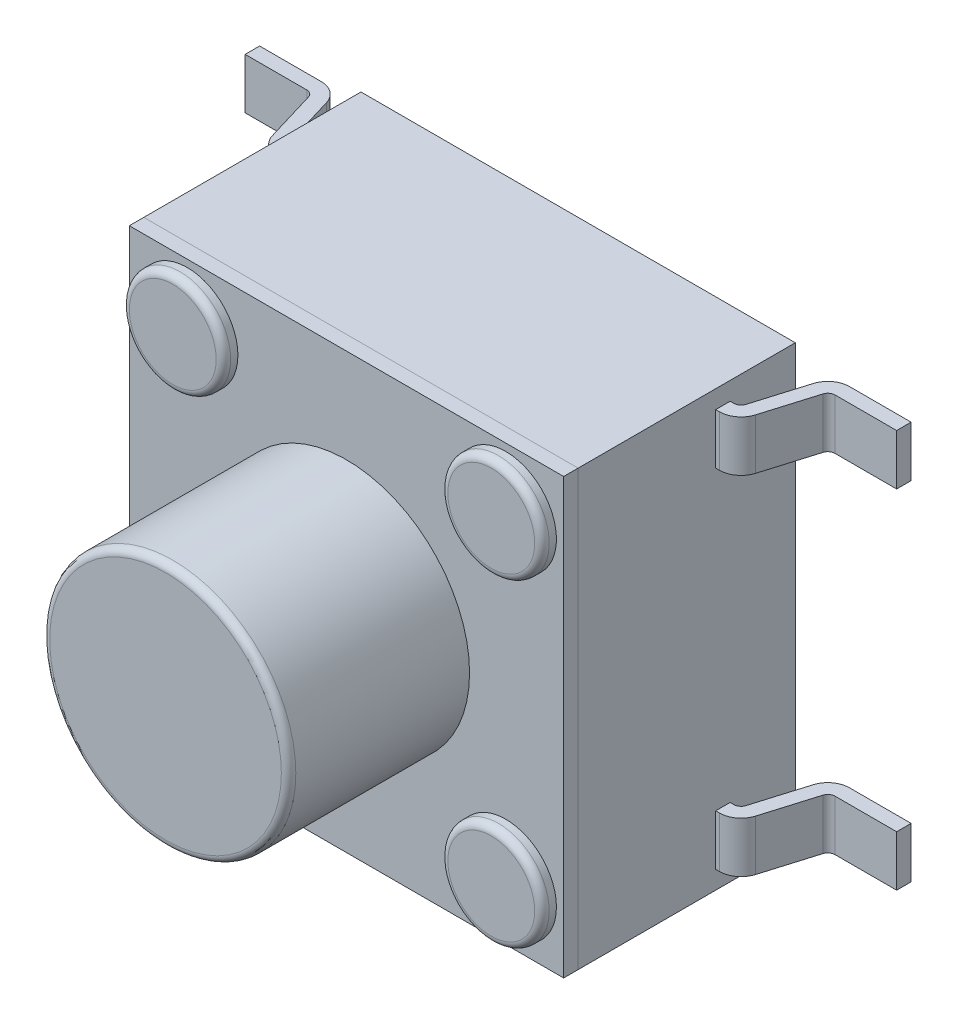
SolidWorks part; units mm, degrees
ref_plane "前视基准面" through (0, 0, 0) normal (0, 0, 1) x (1, 0, 0)
ref_plane "上视基准面" through (0, 0, 0) normal (0, 1, 0) x (1, 0, 0)
ref_plane "右视基准面" through (0, 0, 0) normal (1, 0, 0) x (0, 0, -1)
ref_plane "基准面1" through (0, 0, 0.1) normal (0, 0, 1) x (1, 0, 0)
sketch "草图2" plane through (0, 0, 0.1) normal (0, 0, 1) x (1, 0, 0)
  line L1 (-3, 3) -> (3, 3)
  line L2 (-3, 3) -> (-3, -3)
  line L3 (-3, -3) -> (3, -3)
  line L4 (3, 3) -> (3, -3)
  line L5 (-3, 3) -> (3, -3) construction
  line L6 (-3, -3) -> (3, 3) construction
  point P0 (0, 0)
  dimension "D1" = 6
  dimension "D2" = 6
extrude "凸台-拉伸1" add sketch "草图2" along normal blind 3 contours L1 L4 L3 L2
sketch "草图3" plane through (0, 0, 3.1) normal (0, 0, 1) x (1, 0, 0)
  line L4 (-3, 3) -> (-3, -3)
  line L5 (-3, -3) -> (3, -3)
  line L6 (3, -3) -> (3, 3)
  line L7 (3, 3) -> (-3, 3)
  line L8 (-3, 3) -> (-3, -3)
  line L9 (-3, -3) -> (3, -3)
  line L10 (3, -3) -> (3, 3)
  line L11 (3, 3) -> (-3, 3)
  dimension "D1" = 0
extrude "凸台-拉伸3" add sketch "草图3" along normal blind 0.2 separate body
sketch "草图4" plane through (0, 0, 3.3) normal (0, 0, 1) x (1, 0, 0)
  line L0 (3, 3) -> (-3, 3) construction
  line L2 (-3, 3) -> (-3, -3) construction
  line L3 (-3, 0) -> (3, 0) construction
  line L4 (3, -3) -> (3, 3) construction
  line L5 (0, 3) -> (0, -3) construction
  line L6 (-3, -3) -> (3, -3) construction
  circle A0 centre (-2.2, 2.2) radius 0.7
  circle A1 centre (2.2, 2.2) radius 0.7
  circle A2 centre (2.2, -2.2) radius 0.7
  circle A3 centre (-2.2, -2.2) radius 0.7
  dimension "D1" = 1.4
  dimension "D2" = 0.8
  dimension "D3" = 0.8
extrude "凸台-拉伸4" add sketch "草图4" along normal blind 0.2 separate body
fillet "圆角1" radius 0.1 1 edges at (-2.9, -2.2, 3.5)
fillet "圆角2" radius 0.1 1 edges at (-1.5, 2.2, 3.5)
fillet "圆角3" radius 0.1 1 edges at (1.5, 2.2, 3.5)
fillet "圆角4" radius 0.1 1 edges at (2.9, -2.2, 3.5)
sketch "草图5" plane through (0, 0, 3.3) normal (0, 0, 1) x (1, 0, 0)
  circle A0 centre (0, 0) radius 1.7
  dimension "D1" = 3.4
extrude "凸台-拉伸5" add sketch "草图5" along normal blind 2.5 separate body
fillet "圆角5" radius 0.1 1 edges at (1.7, 0, 5.8)
sketch "草图6" plane through (-3, 0, 0) normal (-1, 0, 0) x (0, 0, 1)
  line L0 (0.1, 3) -> (0.1, -3) construction
  line L1 (1.2, -2.05) -> (1, -2.05)
  line L2 (1.2, -2.05) -> (1.2, -2.75)
  line L3 (1.2, -2.75) -> (1, -2.75)
  line L4 (1, -2.05) -> (1, -2.75)
  line L5 (1.2, -2.05) -> (1, -2.75) construction
  line L6 (1.2, -2.75) -> (1, -2.05) construction
  line L7 (3.1, -3) -> (0.1, -3) construction
  line L8 (0, 0) -> (7.9472, 0) construction
  line L9 (1.2, 2.75) -> (1, 2.75)
  line L10 (1, 2.05) -> (1, 2.75)
  line L11 (1.2, 2.05) -> (1.2, 2.75)
  line L12 (1.2, 2.05) -> (1, 2.05)
  point P0 (1.1, -2.4)
  dimension "D1" = 0.7
  dimension "D2" = 0.2
  dimension "D3" = 1
  dimension "D4" = 0.6
ref_plane "基准面2" through (0, -2.4, 0) normal (0, 1, 0) x (1, 0, 0)
sketch "草图7" plane through (0, -2.4, 0) normal (0, 1, 0) x (1, 0, 0)
  line L0 (-3.4572, -0.2425) -> (-3.2428, -0.9575)
  line L1 (-3.6488, -0.1) -> (-4.5, -0.1)
  line L2 (0.389, 0) -> (-5.8203, 0) construction
  line L3 (-3, -3.1) -> (-3, -0.1) construction
  line L4 (-3.0512, -1.1) -> (-3, -1.1)
  arc A0 (-3.6488, -0.1) -> (-3.4572, -0.2425) centre (-3.6488, -0.3) cw
  arc A1 (-3.2428, -0.9575) -> (-3.0512, -1.1) centre (-3.0512, -0.9) ccw
  point P11 (-3.5, -0.1)
  point P14 (-3.5, -0.1)
  point P17 (-3.2, -1.1)
  dimension "D4" = 0.2
  dimension "D5" = 0.2
  dimension "D1" = 0.1
  dimension "D2" = 1.5
  dimension "D3" = 1
sweep "扫描1" add profiles "草图6" path "草图7"
mirror "镜向1" about plane through (0, 0, 0) normal (1, 0, 0) of "扫描1"
